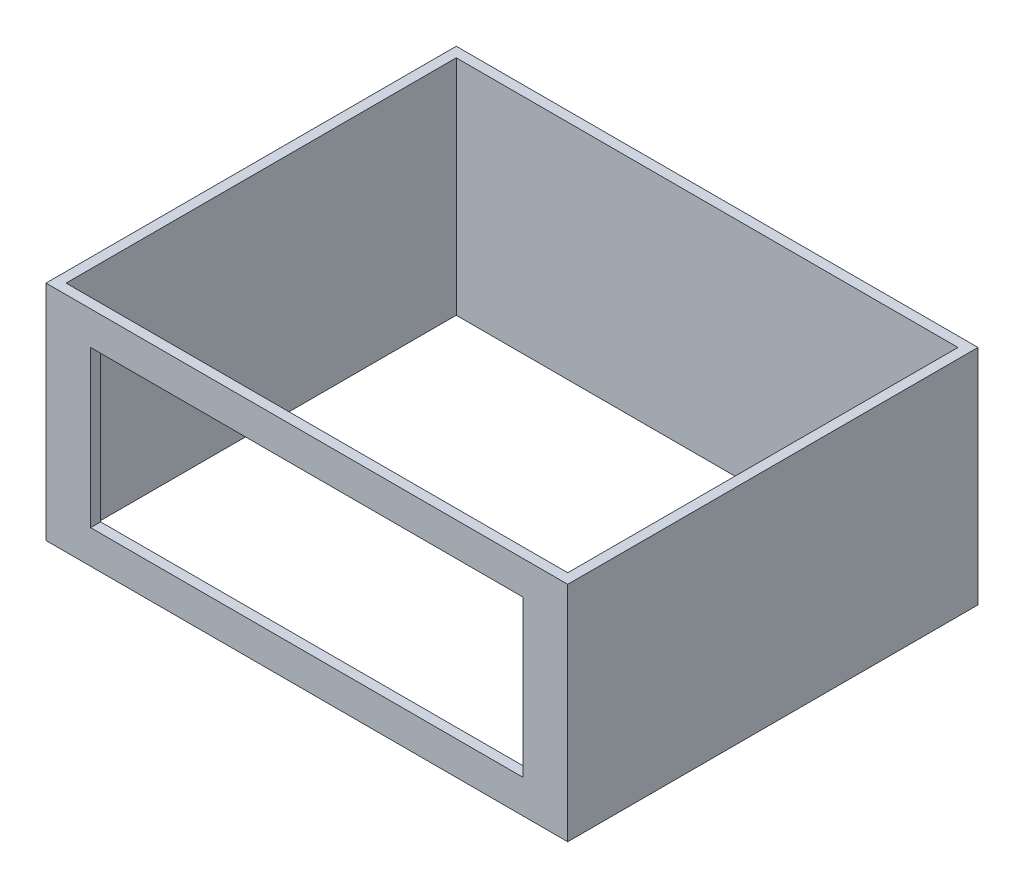
SolidWorks part; units mm, degrees
ref_plane "前视基准面" through (0, 0, 0) normal (0, 0, 1) x (1, 0, 0)
ref_plane "上视基准面" through (0, 0, 0) normal (0, 1, 0) x (1, 0, 0)
ref_plane "右视基准面" through (0, 0, 0) normal (1, 0, 0) x (0, 0, -1)
sketch "草图1" plane through (0, 0, 0) normal (0, 1, 0) x (1, 0, 0)
  line L0 (5.0769, 18) -> (5.0769, -718)
  line L1 (23.0769, 0) -> (923.0769, 0)
  line L2 (23.0769, 0) -> (23.0769, -700)
  line L3 (23.0769, -700) -> (923.0769, -700)
  line L4 (923.0769, 0) -> (923.0769, -700)
  line L5 (5.0769, -718) -> (941.0769, -718)
  line L6 (941.0769, 18) -> (941.0769, -718)
  line L7 (5.0769, 18) -> (941.0769, 18)
  dimension "D1" = 900
  dimension "D2" = 700
  dimension "D3" = 18
extrude "凸台-拉伸1" add sketch "草图1" along normal blind 400
sketch "草图2" plane through (0, 0, 718) normal (0, 0, 1) x (1, 0, 0)
  line L0 (5.0769, 0) -> (941.0769, 0) construction
  line L1 (861.0769, 60) -> (85.0769, 60)
  line L2 (861.0769, 60) -> (861.0769, 340)
  line L3 (861.0769, 340) -> (85.0769, 340)
  line L4 (85.0769, 60) -> (85.0769, 340)
  line L10 (861.0769, 60) -> (861.0769, 0)
  line L11 (861.0769, 340) -> (861.0769, 400)
  line L12 (5.0769, 400) -> (941.0769, 400) construction
  line L13 (941.0769, 400) -> (941.0769, 0) construction
  line L14 (5.0769, 400) -> (5.0769, 0) construction
  dimension "D1" = 60
  dimension "D2" = 80
  dimension "D3" = 80
extrude "切除-拉伸1" cut sketch "草图2" against normal blind 179 contours L4 L1 L2 L3
